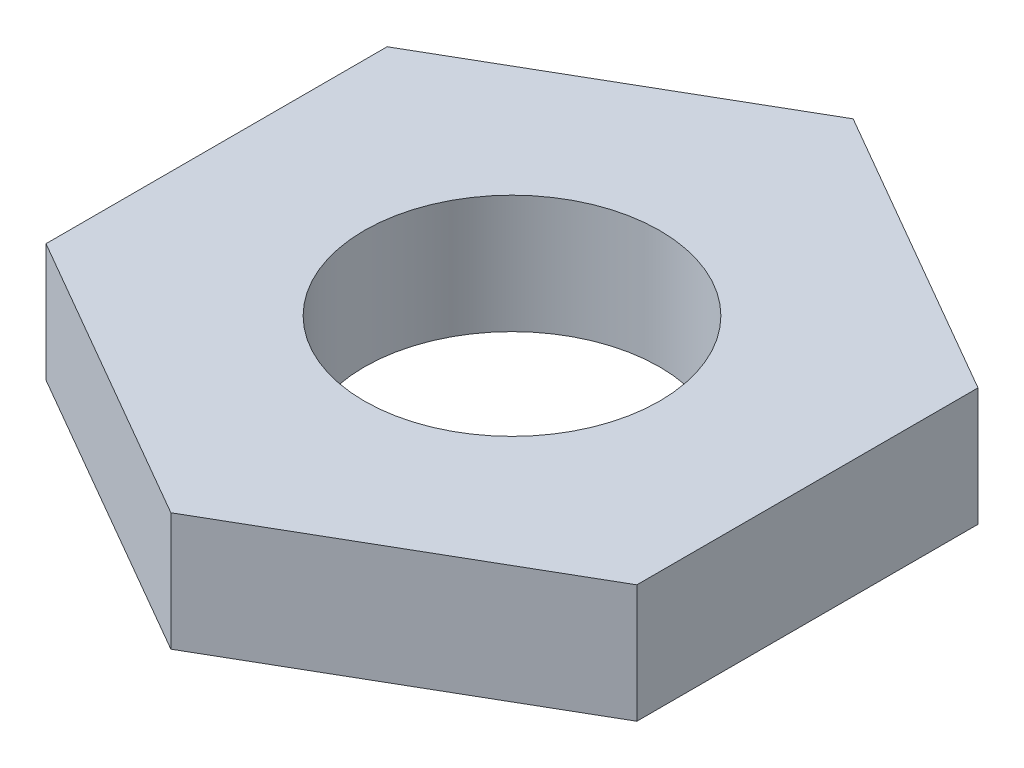
SolidWorks part; units mm, degrees
ref_plane "Front Plane" through (0, 0, 0) normal (0, 0, 1) x (1, 0, 0)
ref_plane "Top Plane" through (0, 0, 0) normal (0, 1, 0) x (1, 0, 0)
ref_plane "Right Plane" through (0, 0, 0) normal (1, 0, 0) x (0, 0, -1)
sketch "Sketch1" plane through (0, 0, 0) normal (0, 1, 0) x (1, 0, 0)
  line L1 (0, 7.3323) -> (-6.35, 3.6662)
  line L2 (-6.35, 3.6662) -> (-6.35, -3.6662)
  line L3 (-6.35, -3.6662) -> (0, -7.3323)
  line L4 (0, -7.3323) -> (6.35, -3.6662)
  line L5 (6.35, -3.6662) -> (6.35, 3.6662)
  line L6 (6.35, 3.6662) -> (0, 7.3323)
  circle A0 centre (0, 0) radius 6.35 construction
  circle A1 centre (0, 0) radius 3.175
  dimension "D1" = 12.7
  dimension "D2" = 6.35
extrude "Boss-Extrude1" add sketch "Sketch1" along normal blind 2.54
